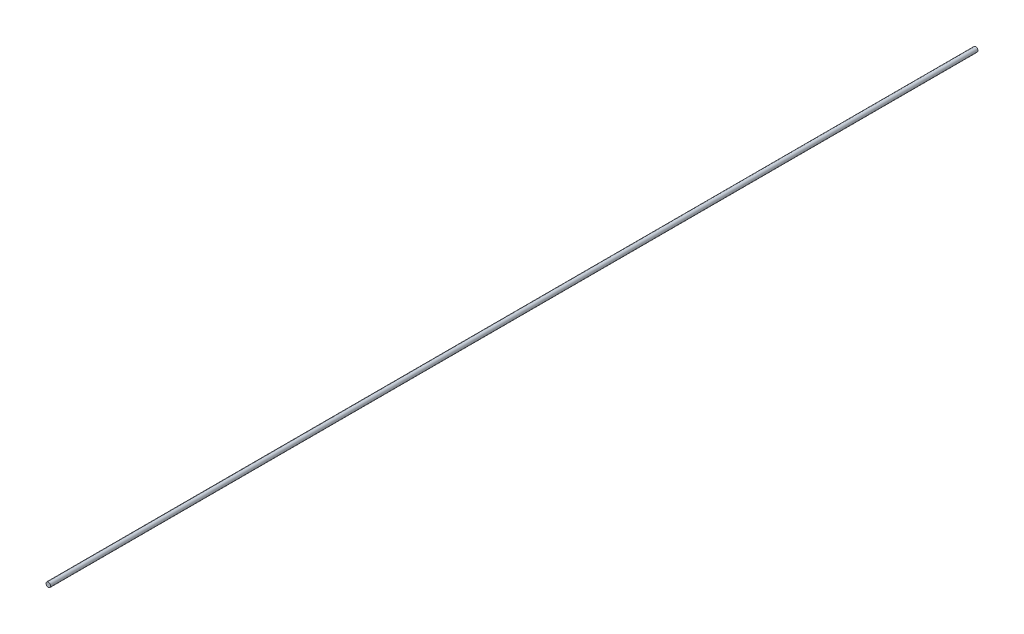
SolidWorks part; units mm, degrees
ref_plane "Front Plane" through (0, 0, 0) normal (0, 0, 1) x (1, 0, 0)
ref_plane "Top Plane" through (0, 0, 0) normal (0, 1, 0) x (1, 0, 0)
ref_plane "Right Plane" through (0, 0, 0) normal (1, 0, 0) x (0, 0, -1)
sketch "Sketch1" plane through (0, 0, 0) normal (0, 0, 1) x (1, 0, 0)
  circle A0 centre (0, 0) radius 0.25
  dimension "D1" = 0.5
extrude "Boss-Extrude1" add sketch "Sketch1" along normal blind 100
